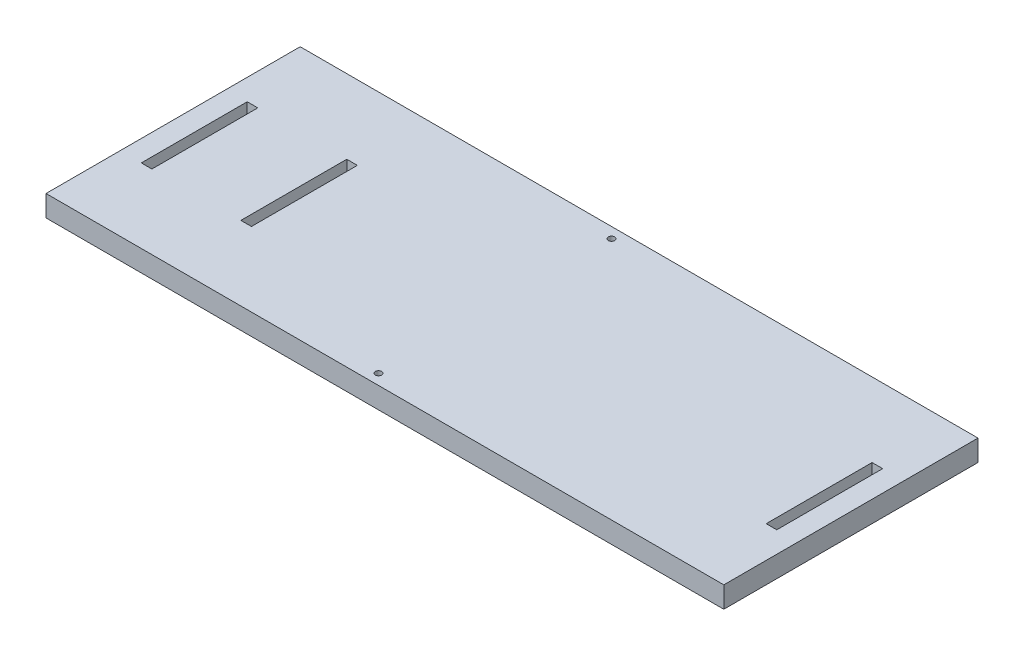
SolidWorks part; units mm, degrees
ref_plane "Front Plane" through (0, 0, 0) normal (0, 0, 1) x (1, 0, 0)
ref_plane "Top Plane" through (0, 0, 0) normal (0, 1, 0) x (1, 0, 0)
ref_plane "Right Plane" through (0, 0, 0) normal (1, 0, 0) x (0, 0, -1)
sketch "Sketch1" plane through (0, 0, 0) normal (0, 1, 0) x (1, 0, 0)
  line L1 (0, 0) -> (320, 0)
  line L2 (0, 0) -> (0, -80)
  line L3 (0, -80) -> (320, -80)
  line L4 (320, 0) -> (320, -80)
  line L5 (10, -15) -> (15, -15)
  line L6 (10, -15) -> (10, -65)
  line L7 (10, -65) -> (15, -65)
  line L8 (15, -15) -> (15, -65)
  line L9 (57, -15) -> (62, -15)
  line L10 (57, -15) -> (57, -65)
  line L11 (57, -65) -> (62, -65)
  line L12 (62, -15) -> (62, -65)
  line L13 (305, -15) -> (310, -15)
  line L14 (305, -15) -> (305, -65)
  line L15 (305, -65) -> (310, -65)
  line L16 (310, -15) -> (310, -65)
  point P17 (10, -40)
  point P18 (62, -40)
  point P19 (310, -40)
  dimension "D1" = 320
  dimension "D2" = 80
  dimension "D3" = 50
  dimension "D4" = 50
  dimension "D5" = 50
  dimension "D6" = 5
  dimension "D7" = 5
  dimension "D8" = 5
  dimension "D9" = 10
  dimension "D10" = 10
  dimension "D11" = 243
  dimension "D12" = 40
  dimension "D13" = 40
  dimension "D14" = 40
extrude "Boss-Extrude1" add sketch "Sketch1" along normal blind 10
sketch "Sketch2" plane through (0, 10, 0) normal (0, 1, 0) x (1, 0, 0)
  line L1 (0, 20) -> (320, 20)
  line L2 (0, 20) -> (0, 0)
  line L3 (0, 0) -> (320, 0)
  line L4 (320, 20) -> (320, 0)
  line L5 (0, -80) -> (320, -80)
  line L6 (0, -80) -> (0, -100)
  line L7 (0, -100) -> (320, -100)
  line L8 (320, -80) -> (320, -100)
  dimension "D1" = 20
  dimension "D2" = 20
extrude "Boss-Extrude2" add sketch "Sketch2" against normal blind 10
sketch "Sketch3" plane through (0, 10, 0) normal (0, 1, 0) x (1, 0, 0)
  line L0 (0, -40) -> (322.419, -40) construction
  line L1 (0, 20) -> (0, -100) construction
  line L3 (62, -65) -> (62, -15) construction
  circle A0 centre (152, 15) radius 1.5
  circle A1 centre (152, -95) radius 1.5
  dimension "D1" = 3
  dimension "D2" = 55
  dimension "D3" = 90
extrude "Cut-Extrude1" cut sketch "Sketch3" against normal blind 10
equation "\"D4@Sketch1\"=\"D3@Sketch1\""
equation "\"D5@Sketch1\"=\"D3@Sketch1\""
equation "\"D10@Sketch1\"=\"D9@Sketch1\""
equation "\"D13@Sketch1\"=\"D12@Sketch1\""
equation "\"D14@Sketch1\"=\"D13@Sketch1\""
